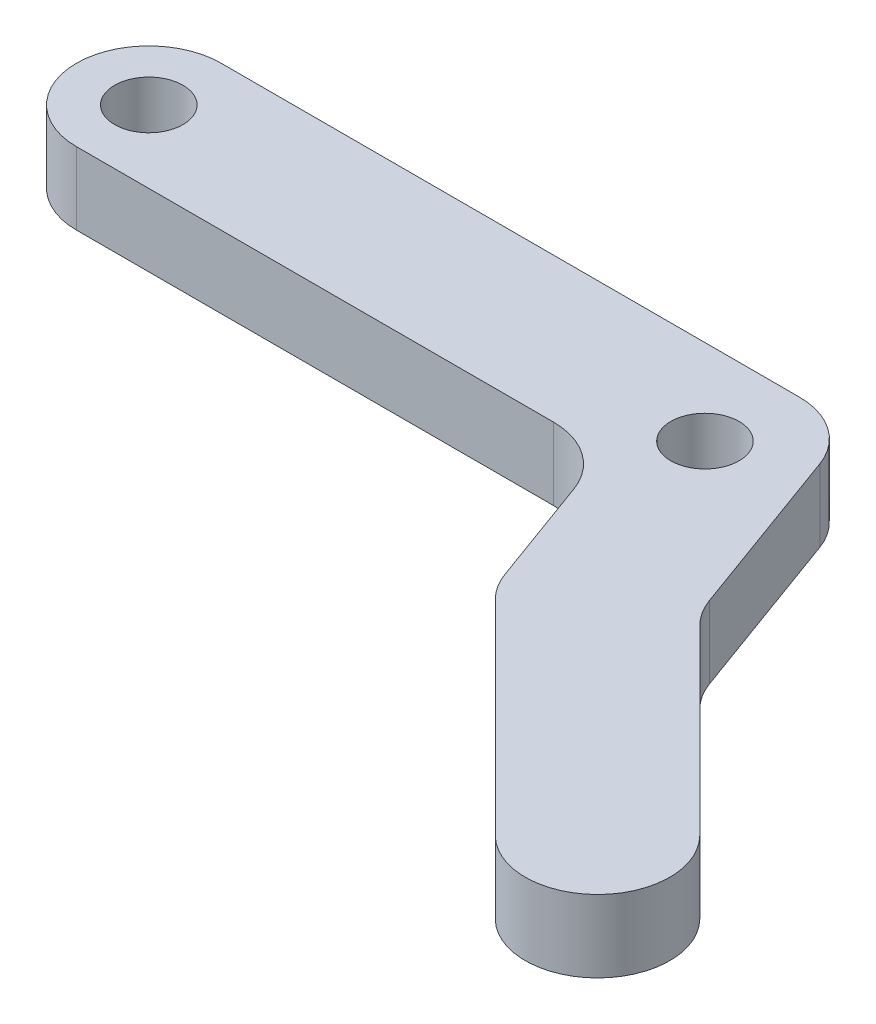
SolidWorks part; units mm, degrees
ref_plane "Front Plane" through (0, 0, 0) normal (0, 0, 1) x (1, 0, 0)
ref_plane "Top Plane" through (0, 0, 0) normal (0, 1, 0) x (1, 0, 0)
ref_plane "Right Plane" through (0, 0, 0) normal (1, 0, 0) x (0, 0, -1)
sketch "Sketch1" plane through (0, 0, 0) normal (0, 1, 0) x (1, 0, 0)
  line L0 (0, 0) -> (25.4, 0) construction
  line L1 (25.4, 0) -> (28.6577, -8.9506) construction
  line L2 (0, -3.175) -> (20.9537, -3.175)
  line L3 (23.9372, -5.2641) -> (25.6742, -10.0365)
  line L4 (0, 3.175) -> (25.4, 3.175)
  line L5 (28.3835, 1.0859) -> (31.1598, -6.5418)
  line L6 (0, -3.175) -> (23.1768, -3.175) construction
  line L7 (23.1768, -3.175) -> (25.6742, -10.0365) construction
  line L8 (0, 3.175) -> (27.6232, 3.175) construction
  line L9 (27.6232, 3.175) -> (31.6413, -7.8647) construction
  line L10 (22.7748, -3.7492) -> (27.2211, 2.6008) construction
  line L11 (28.6577, -8.9506) -> (37.638, -17.9308) construction
  line L12 (31.8982, -7.7009) -> (39.8831, -15.6858)
  line L13 (35.3929, -20.1759) -> (26.4127, -11.1956)
  arc A0 (0, -3.175) -> (0, 3.175) centre (0, 0) cw
  arc A2 (20.9537, -3.175) -> (23.9372, -5.2641) centre (20.9537, -6.35) cw
  arc A3 (25.4, 3.175) -> (28.3835, 1.0859) centre (25.4, 0) cw
  circle A4 centre (24.9979, -0.5742) radius 1.5
  circle A5 centre (0, 0) radius 1.5
  arc A6 (39.8831, -15.6858) -> (35.3929, -20.1759) centre (37.638, -17.9308) cw
  arc A7 (25.6742, -10.0365) -> (26.4127, -11.1956) centre (28.6577, -8.9506) ccw
  arc A8 (31.1598, -6.5418) -> (31.8982, -7.7009) centre (34.1433, -5.4559) ccw
  dimension "D6" = 3
  dimension "D8" = 135
  dimension "D1" = 9.525
  dimension "D2" = 25.4
  dimension "D5" = 110
  dimension "D7" = 12.7
  dimension "D3" = 3.175
  dimension "D4" = 3.175
extrude "Boss-Extrude1" add sketch "Sketch1" along normal blind 3.175
sketch "Sketch2" [suppressed] plane through (0, 0, 0) normal (0, -1, 0) x (1, 0, 0)
  line L0 (23.4659, 3.9961) -> (22.2511, 3.4522)
  line L7 (0, -3.175) -> (25.4, -3.175)
  line L8 (28.3835, -1.0859) -> (31.1598, 6.5418)
  line L9 (31.8982, 7.7009) -> (39.8831, 15.6858)
  line L10 (35.3929, 20.1759) -> (26.4127, 11.1956)
  line L11 (25.6742, 10.0365) -> (23.9372, 5.2641)
  line L12 (20.9537, 3.175) -> (0, 3.175)
  line L14 (28.521, -0.7081) -> (31.1598, 6.5418)
  line L15 (31.8982, 7.7009) -> (39.8831, 15.6858)
  line L16 (35.3929, 20.1759) -> (26.4127, 11.1956)
  line L17 (25.6742, 10.0365) -> (23.9372, 5.2641)
  arc A0 (28.521, -0.7081) -> (23.4659, 3.9961) centre (24.9979, 0.5742) ccw
  arc A1 (20.9537, 3.175) -> (23.9372, 5.2641) centre (20.9537, 6.35) ccw construction
  arc A8 (0, 3.175) -> (0, -3.175) centre (0, 0) ccw
  arc A9 (25.4, -3.175) -> (28.3835, -1.0859) centre (25.4, 0) ccw
  arc A10 (31.8982, 7.7009) -> (31.1598, 6.5418) centre (34.1433, 5.4559) ccw
  arc A11 (39.8831, 15.6858) -> (35.3929, 20.1759) centre (37.638, 17.9308) ccw
  arc A12 (26.4127, 11.1956) -> (25.6742, 10.0365) centre (28.6577, 8.9506) ccw
  arc A13 (20.9537, 3.175) -> (23.9372, 5.2641) centre (20.9537, 6.35) ccw
  arc A16 (31.8982, 7.7009) -> (31.1598, 6.5418) centre (34.1433, 5.4559) ccw
  arc A17 (39.8831, 15.6858) -> (35.3929, 20.1759) centre (37.638, 17.9308) ccw
  arc A18 (26.4127, 11.1956) -> (25.6742, 10.0365) centre (28.6577, 8.9506) ccw
  arc A19 (22.2511, 3.4522) -> (23.9372, 5.2641) centre (20.9537, 6.35) ccw
  dimension "D1" = 0
extrude "Cut-Extrude1" [suppressed] cut sketch "Sketch2" against normal through all
